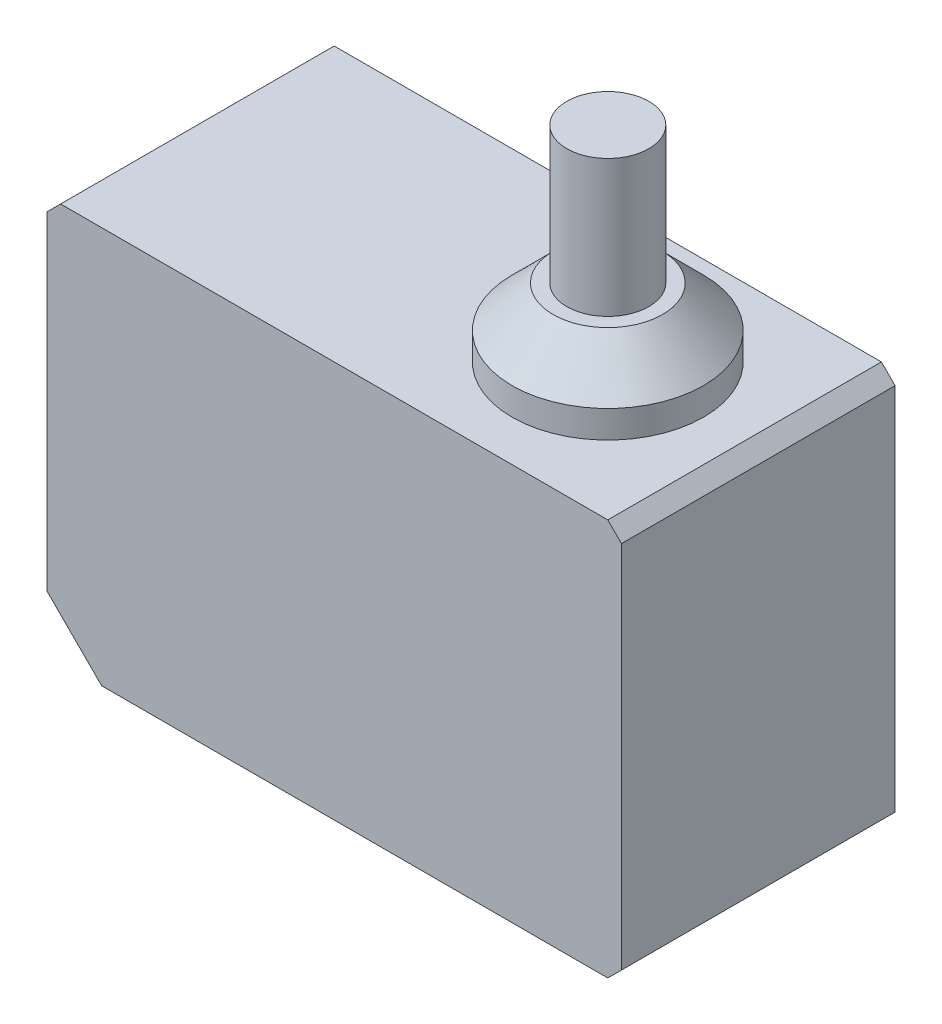
SolidWorks part; units mm, degrees
ref_plane "Front Plane" through (0, 0, 0) normal (0, 0, 1) x (1, 0, 0)
ref_plane "Top Plane" through (0, 0, 0) normal (0, 1, 0) x (1, 0, 0)
ref_plane "Right Plane" through (0, 0, 0) normal (1, 0, 0) x (0, 0, -1)
sketch "Sketch1" plane through (0, 0, 0) normal (0, 0, 1) x (1, 0, 0)
  line L1 (0, 0) -> (42, 0)
  line L2 (0, 0) -> (0, 29)
  line L3 (0, 29) -> (42, 29)
  line L4 (42, 0) -> (42, 29)
  dimension "D1" = 29
  dimension "D2" = 42
extrude "Boss-Extrude1" add sketch "Sketch1" along normal blind 20
chamfer "Chamfer1" distance 4 angle 45 1 edges at (0, 0, 10)
chamfer "Chamfer2" distance 1 angle 45 2 edges at (42, 29, 10) (0, 29, 10)
chamfer "Chamfer3" distance 1 angle 45 1 edges at (42, 0, 10)
sketch "Sketch4" plane through (0, 29, 0) normal (0, 1, 0) x (1, 0, 0)
  line L0 (1, 0) -> (1, -20) construction
  line L1 (41, -20) -> (1, -20) construction
  line L2 (1, 0) -> (1, -20) construction
  line L3 (1, -20) -> (41, -20) construction
  line L4 (41, -20) -> (41, 0) construction
  line L5 (1, -10) -> (42.1, -10) construction
  circle A0 centre (31, -10) radius 7
  dimension "D1" = 14
  dimension "D2" = 10
extrude "Boss-Extrude2" add sketch "Sketch4" along normal blind 5
chamfer "Chamfer4" distance 3 angle 45 1 edges at (31, 34, 17)
sketch "Sketch5" plane through (0, 34, 0) normal (0, 1, 0) x (1, 0, 0)
  circle A0 centre (31, -10) radius 3
  dimension "D1" = 6
extrude "Boss-Extrude3" add sketch "Sketch5" along normal blind 10
